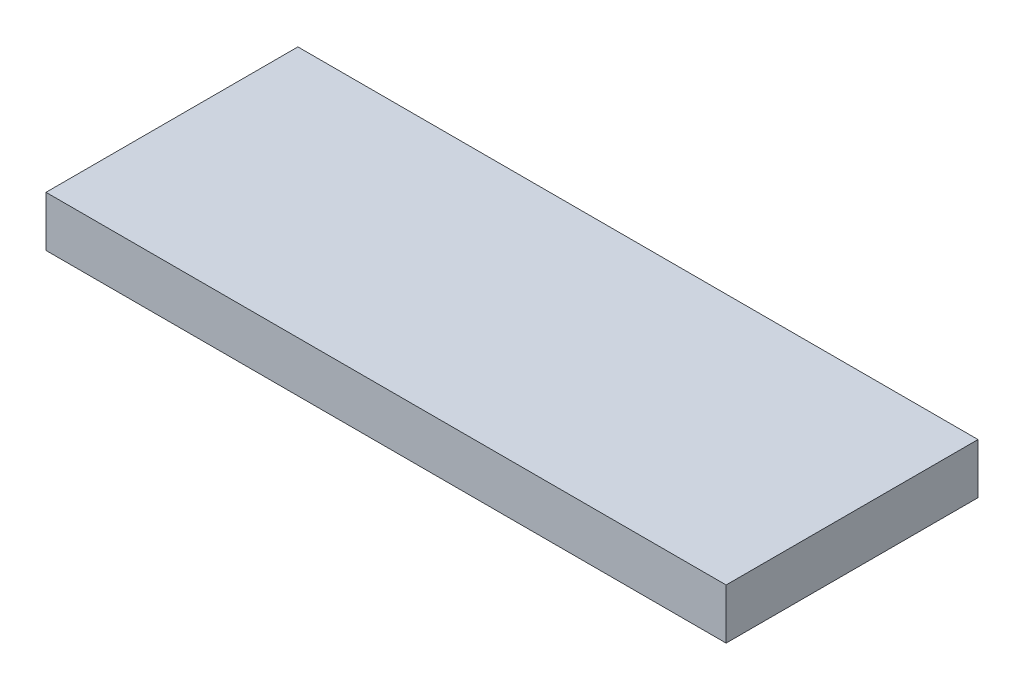
SolidWorks part; units mm, degrees
ref_plane "Front" through (0, 0, 0) normal (0, 0, 1) x (1, 0, 0)
ref_plane "Top" through (0, 0, 0) normal (0, 1, 0) x (1, 0, 0)
ref_plane "Right" through (0, 0, 0) normal (1, 0, 0) x (0, 0, -1)
sketch "草图2" plane through (0, 0, 0) normal (0, 1, 0) x (1, 0, 0)
  line L1 (0, 0) -> (54, 0)
  line L2 (0, 0) -> (0, -20)
  line L3 (0, -20) -> (54, -20)
  line L4 (54, 0) -> (54, -20)
  dimension "D1" = 54
  dimension "D2" = 20
extrude "凸台-拉伸1" add sketch "草图2" along normal blind 4
